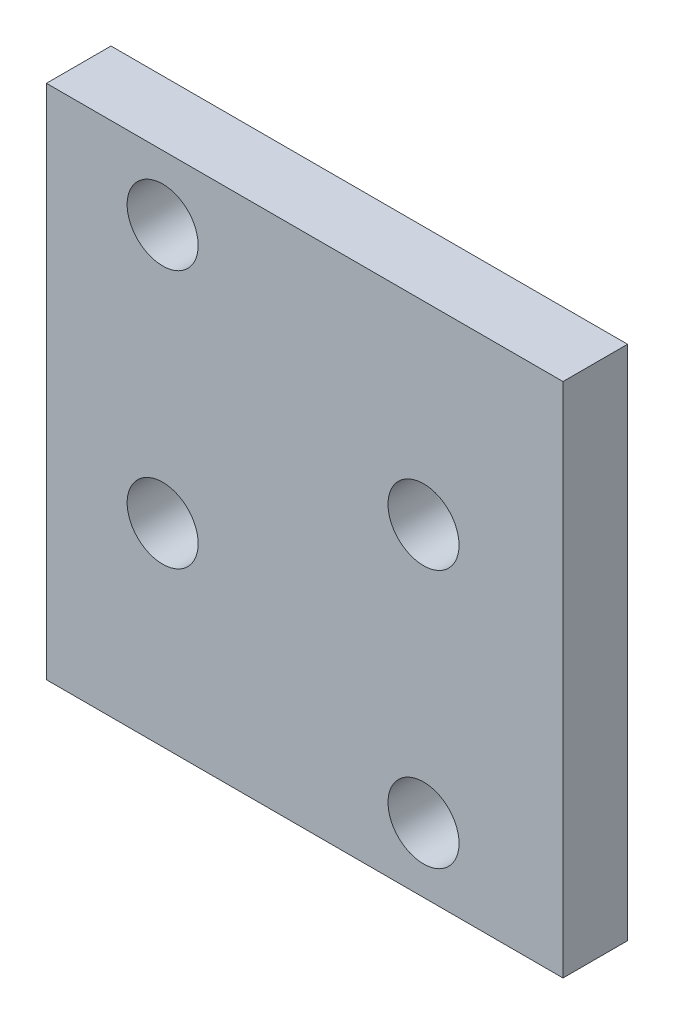
SolidWorks part; units mm, degrees
material "Настроенная пользователем пластмасса"
ref_plane "Спереди" through (0, 0, 0) normal (0, 0, 1) x (1, 0, 0)
ref_plane "Сверху" through (0, 0, 0) normal (0, 1, 0) x (1, 0, 0)
ref_plane "Справа" through (0, 0, 0) normal (1, 0, 0) x (0, 0, -1)
sketch "Эскиз1" plane through (0, 0, 0) normal (0, 0, 1) x (1, 0, 0)
  line L1 (0, 0) -> (40, 0)
  line L2 (0, 0) -> (0, 40)
  line L3 (0, 40) -> (40, 40)
  line L4 (40, 0) -> (40, 40)
  dimension "D1" = 40
  dimension "D2" = 40
extrude "Бобышка-Вытянуть1" add sketch "Эскиз1" along normal blind 5
sketch "Эскиз2" plane through (0, 0, 5) normal (0, 0, 1) x (1, 0, 0)
  line L0 (9, 40) -> (9, 0) construction
  line L1 (40, 40) -> (0, 40) construction
  line L2 (0, 0) -> (40, 0) construction
  line L3 (29.2, 40) -> (29.2, 0) construction
  line L4 (3.8588, 35) -> (15.1726, 35) construction
  line L5 (3.8588, 15) -> (14.0285, 15) construction
  line L6 (26.8677, 5) -> (35.7662, 5) construction
  line L7 (25.2151, 25) -> (37.673, 25) construction
  circle A0 centre (9, 35) radius 2.75
  circle A1 centre (9, 15) radius 2.75
  circle A2 centre (29.2, 5) radius 2.75
  circle A3 centre (29.2, 25) radius 2.75
  dimension "D7" = 5.5
  dimension "D8" = 5.5
  dimension "D9" = 5.5
  dimension "D10" = 5.5
  dimension "D1" = 9
  dimension "D2" = 10.8
  dimension "D3" = 5
  dimension "D4" = 15
  dimension "D5" = 5
  dimension "D6" = 15
extrude "Вырез-Вытянуть1" cut sketch "Эскиз2" against normal through all
